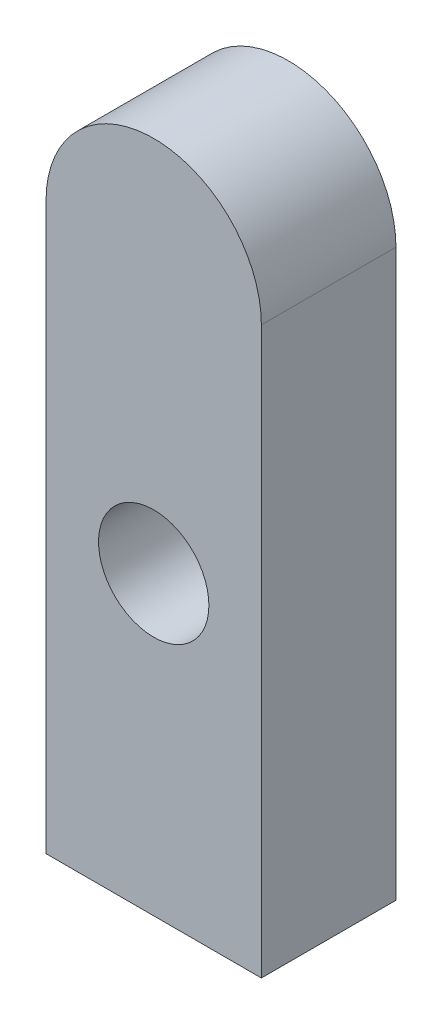
SolidWorks part; units mm, degrees
ref_plane "정면" through (0, 0, 0) normal (0, 0, 1) x (1, 0, 0)
ref_plane "윗면" through (0, 0, 0) normal (0, 1, 0) x (1, 0, 0)
ref_plane "우측면" through (0, 0, 0) normal (1, 0, 0) x (0, 0, -1)
sketch "스케치1" plane through (0, 0, 0) normal (0, 0, 1) x (1, 0, 0)
  line L0 (0, 0) -> (0, 10) construction
  line L1 (-4, 0) -> (-4, 10)
  line L2 (4, 0) -> (4, 10)
  line L3 (-4, 0) -> (-4, -11.0146)
  line L4 (-4, -11.0146) -> (4, -11.0146)
  line L5 (4, -11.0146) -> (4, 0)
  circle A0 centre (0, 0) radius 2.05
  arc A2 (4, 10) -> (-4, 10) centre (0, 10) ccw
  point P3 (0, 5)
  dimension "D1" = 4.1
  dimension "D2" = 10
extrude "보스-돌출1" add sketch "스케치1" along normal mid plane 5
